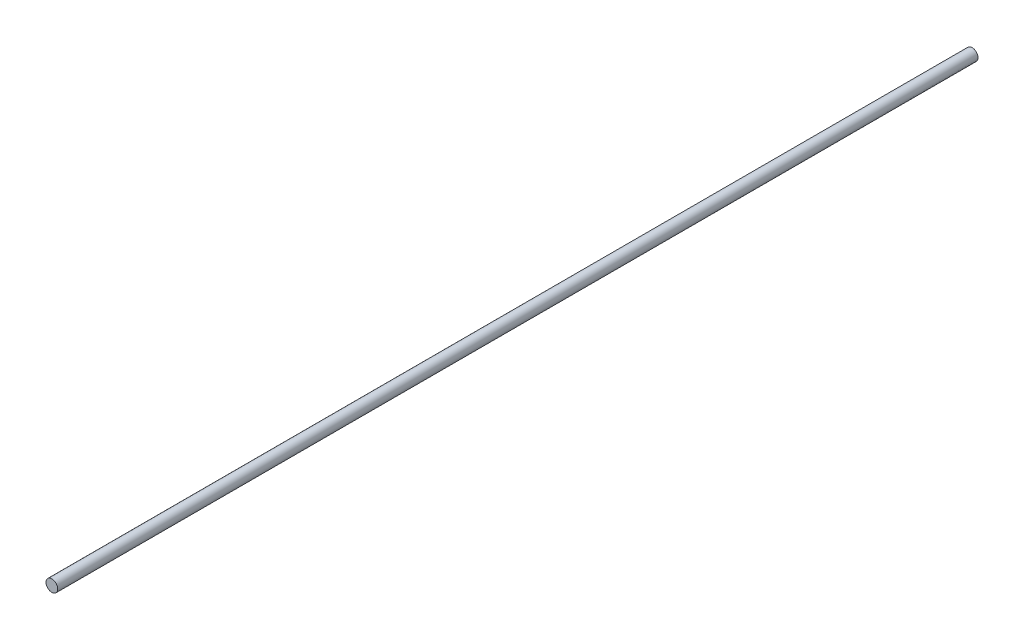
SolidWorks part; units mm, degrees
ref_plane "Plan de face" through (0, 0, 0) normal (0, 0, 1) x (1, 0, 0)
ref_plane "Plan de dessus" through (0, 0, 0) normal (0, 1, 0) x (1, 0, 0)
ref_plane "Plan de droite" through (0, 0, 0) normal (1, 0, 0) x (0, 0, -1)
sketch "Esquisse1" plane through (0, 0, 0) normal (0, 0, 1) x (1, 0, 0)
  circle A0 centre (0, 0) radius 5
  dimension "D1" = 10
extrude "Boss.-Extru.1" add sketch "Esquisse1" along normal blind 785
